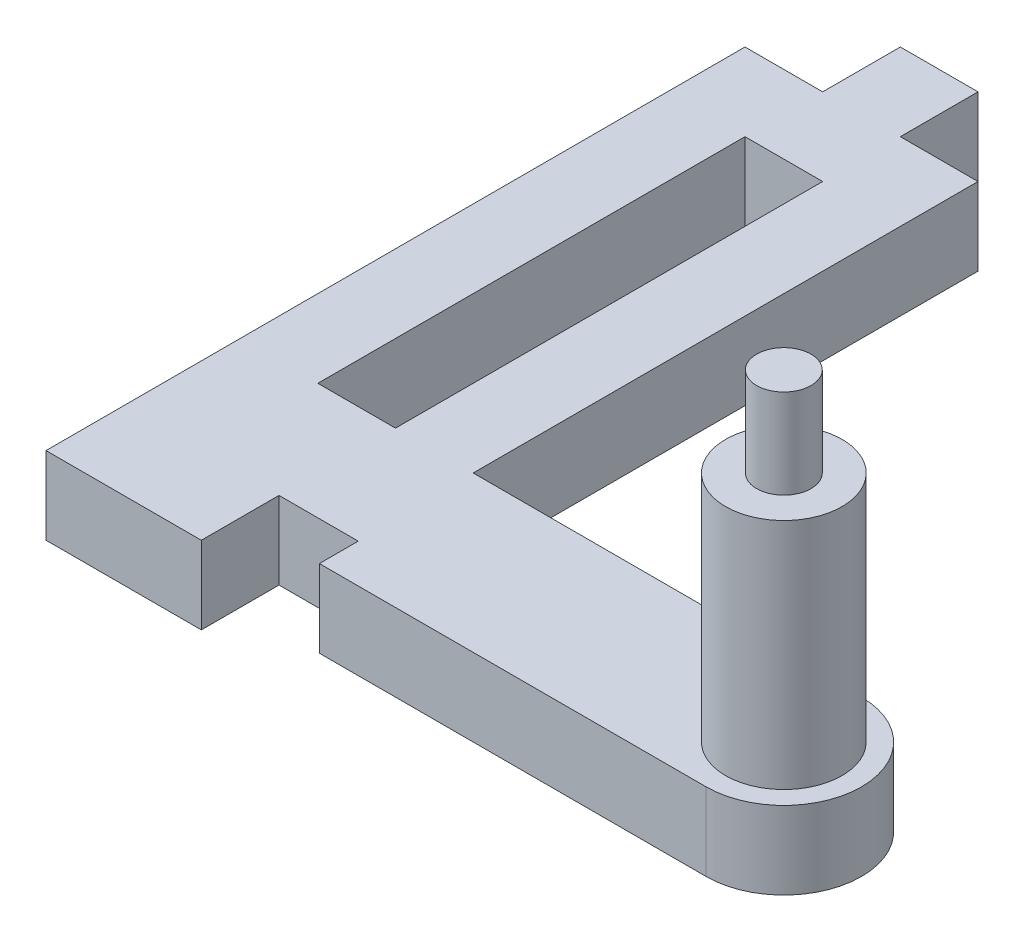
SolidWorks part; units mm, degrees
ref_plane "Front Plane" through (0, 0, 0) normal (0, 0, 1) x (1, 0, 0)
ref_plane "Top Plane" through (0, 0, 0) normal (0, 1, 0) x (1, 0, 0)
ref_plane "Right Plane" through (0, 0, 0) normal (1, 0, 0) x (0, 0, -1)
sketch "Sketch1" plane through (0, 0, 0) normal (0, 1, 0) x (1, 0, 0)
  line L1 (0, 0) -> (45, 0)
  line L2 (0, 0) -> (0, 12)
  line L3 (0, 12) -> (45, 12)
  line L5 (0, 0) -> (15, 0)
  line L6 (0, 0) -> (0, -5)
  line L7 (0, -5) -> (15, -5)
  line L8 (15, 0) -> (15, -5)
  line L9 (0, 12) -> (24, 12)
  line L10 (0, 12) -> (0, 55.0692)
  line L11 (0, 55.0692) -> (24, 55.0692)
  line L12 (24, 12) -> (24, 55.0692)
  circle A0 centre (45, 6) radius 3
  arc A1 (45, 0) -> (45, 12) centre (45, 6) ccw
  circle A6 centre (12, 53.0692) radius 0.7
  circle A7 centre (21.5263, 36.5692) radius 0.7
  circle A8 centre (2.4737, 36.5692) radius 0.7
  circle A11 centre (12, 42.0692) radius 2
  dimension "D4" = 45
  dimension "D3" = 6
  dimension "D11" = 1.4
  dimension "D1" = 5
  dimension "D2" = 15
  dimension "D5" = 6
  dimension "D13" = 3
sketch "Sketch2" plane through (0, 0, 0) normal (0, 1, 0) x (1, 0, 0)
  line L0 (13.8867, 45.212) -> (13.8867, 40)
  line L1 (0, 0) -> (15, 0)
  line L5 (0, 0) -> (15.1, 0)
  line L6 (0, 0) -> (0, 40)
  line L7 (0, 40) -> (15, 40)
  line L8 (15, 7.5) -> (15, 40)
  line L9 (10, 40) -> (5, 40)
  line L10 (10, 40) -> (10, 45)
  line L11 (10, 45) -> (5, 45)
  line L12 (5, 40) -> (5, 45)
  line L17 (13.3723, 20.2678) -> (35.2318, 32.8884)
  line L18 (35.2318, 32.8884) -> (15, 21.2076)
  line L19 (28.1168, 45.212) -> (36.8437, 51.9084) construction
  line L20 (15, 7.5) -> (40, 7.5)
  line L21 (15.1, 0) -> (15.1, -2.5)
  line L22 (15.1, -2.5) -> (40, -2.5)
  line L24 (15, 7.5) -> (0, 7.5)
  line L25 (5, 35) -> (10, 35)
  line L26 (5, 35) -> (5, 5)
  line L27 (5, 5) -> (10, 5)
  line L28 (10, 35) -> (10, 5)
  line L30 (0, 0) -> (10, 0)
  line L31 (0, 0) -> (0, -5)
  line L32 (0, -5) -> (10, -5)
  line L33 (10, 0) -> (10, -5)
  circle A10 centre (28.1168, 45.212) radius 14.2301
  circle A11 centre (28.1168, 45.212) radius 2
  circle A12 centre (40, 2.5) radius 39.7 construction
  circle A13 centre (28.1168, 45.212) radius 4.6343 construction
  arc A14 (40, -2.5) -> (40, 7.5) centre (40, 2.5) ccw
  circle A15 centre (36.8437, 51.9084) radius 0.7
  circle A16 centre (38.7225, 39.6004) radius 0.7
  circle A17 centre (27.124, 44.1273) radius 0.7
  dimension "D5" = 79.4
  dimension "D6" = 40
  dimension "D7" = 5
  dimension "D8" = 2.5
  dimension "D9" = 60
  dimension "D10" = 5
  dimension "D14" = 52.5
  dimension "D1" = 40
  dimension "D2" = 5
  dimension "D3" = 5
  dimension "D4" = 5
  dimension "D11" = 5
  dimension "D12" = 11
  dimension "D13" = 10
  dimension "D16" = 5
  dimension "D17" = 5
  dimension "D18" = 5
  dimension "D19" = 5
  dimension "D20" = 5.1
  dimension "D21" = 5
  dimension "D15" = 3
extrude "Boss-Extrude1" add sketch "Sketch2" along normal blind 5
sketch "Sketch3" plane through (0, 5, 0) normal (0, 1, 0) x (1, 0, 0)
  circle A0 centre (40, 2.5) radius 3.75
extrude "Boss-Extrude2" add sketch "Sketch3" along normal blind 15
sketch "Sketch4" plane through (0, 20, 0) normal (0, 1, 0) x (1, 0, 0)
  circle A0 centre (40, 2.5) radius 3
  circle A1 centre (40, 2.5) radius 1.75
extrude "Boss-Extrude3" add sketch "Sketch4" along normal blind 5.75 contours A1
